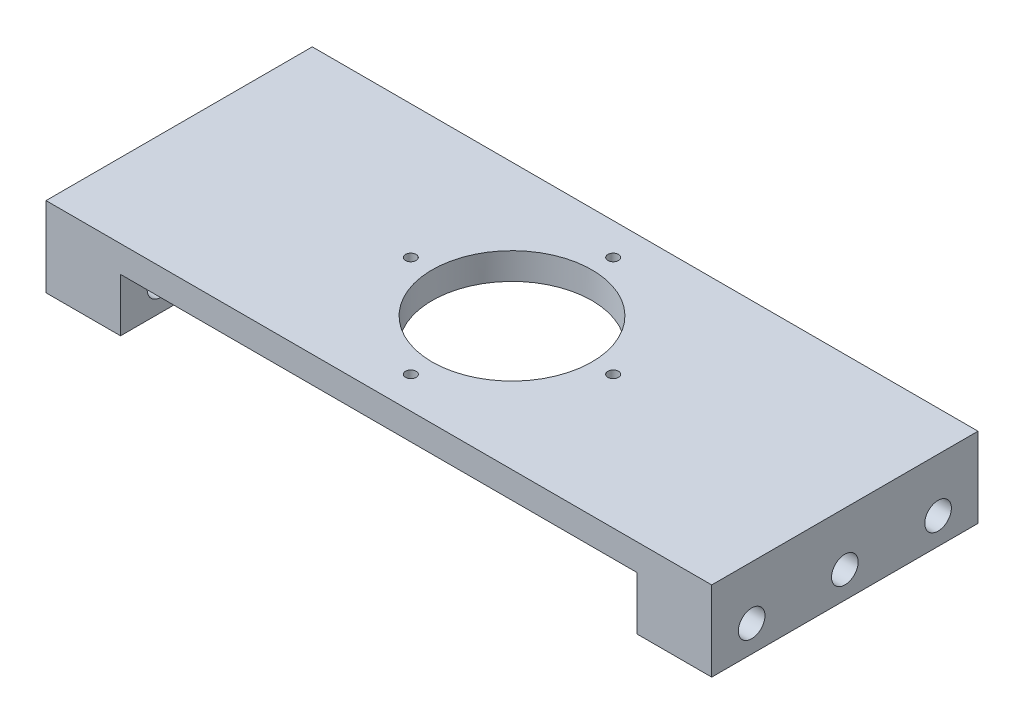
SolidWorks part; units mm, degrees
material "1060 合金"
ref_plane "前视基准面" through (0, 0, 0) normal (0, 0, 1) x (1, 0, 0)
ref_plane "上视基准面" through (0, 0, 0) normal (0, 1, 0) x (1, 0, 0)
ref_plane "右视基准面" through (0, 0, 0) normal (1, 0, 0) x (0, 0, -1)
sketch "草图1" plane through (0, 0, 0) normal (0, 1, 0) x (1, 0, 0)
  line L0 (0, -50) -> (125, -50)
  line L1 (0, -50) -> (-125, -50)
  line L2 (-125, -50) -> (-125, 50)
  line L3 (-125, 50) -> (125, 50)
  line L4 (125, 50) -> (125, -50)
  dimension "D1" = 125
  dimension "D2" = 100
  dimension "110" = 125
  dimension "D3" = 50
  dimension "D4" = 125
extrude "凸台-拉伸1" add sketch "草图1" along normal blind 10
sketch "草图2" plane through (0, 10, 0) normal (0, 1, 0) x (1, 0, 0)
  circle A0 centre (0, 0) radius 30
extrude "切除-拉伸1" cut sketch "草图2" against normal blind 15
sketch "草图4" plane through (0, 0, 0) normal (0, -1, 0) x (1, 0, 0)
  line L0 (-125, 50) -> (-125, -50)
  line L1 (-125, 50) -> (-97, 50)
  line L2 (-97, 50) -> (-97, -50)
  line L3 (125, -50) -> (-125, -50) construction
  line L4 (-97, -50) -> (-125, -50)
  dimension "D1" = 28
  dimension "D2" = 0
  dimension "D3" = 28
extrude "凸台-拉伸2" add sketch "草图4" along normal blind 20
mirror "镜向1" about plane through (0, 0, 0) normal (1, 0, 0) of "凸台-拉伸2"
sketch "草图5" plane through (125, 0, 0) normal (1, 0, 0) x (0, 0, -1)
  line L0 (-50, -20) -> (50, -20) construction
  circle A0 centre (0, -10) radius 5
  circle A1 centre (35, -10) radius 5
  circle A2 centre (-35, -10) radius 5
  dimension "D1" = 10
  dimension "D2" = 10
  dimension "D3" = 10
  dimension "D4" = 35
  dimension "D5" = 35
  dimension "D6" = 0
extrude "切除-拉伸2" cut sketch "草图5" against normal blind 30
mirror "镜向2" about plane through (0, 0, 0) normal (1, 0, 0) of "切除-拉伸2"
sketch "草图6" plane through (0, 10, 0) normal (0, 1, 0) x (1, 0, 0)
  circle A0 centre (0, 38) radius 2
  point P0 (0, 0)
extrude "切除-拉伸4" cut sketch "草图6" against normal blind 10
pattern_circular "阵列(圆周)1" count 4 over 360 about axis through (0, 0, 0) along (0, 1, 0) of "切除-拉伸4"
sketch "草图7" plane through (0, 10, 0) normal (0, 1, 0) x (1, 0, 0)
